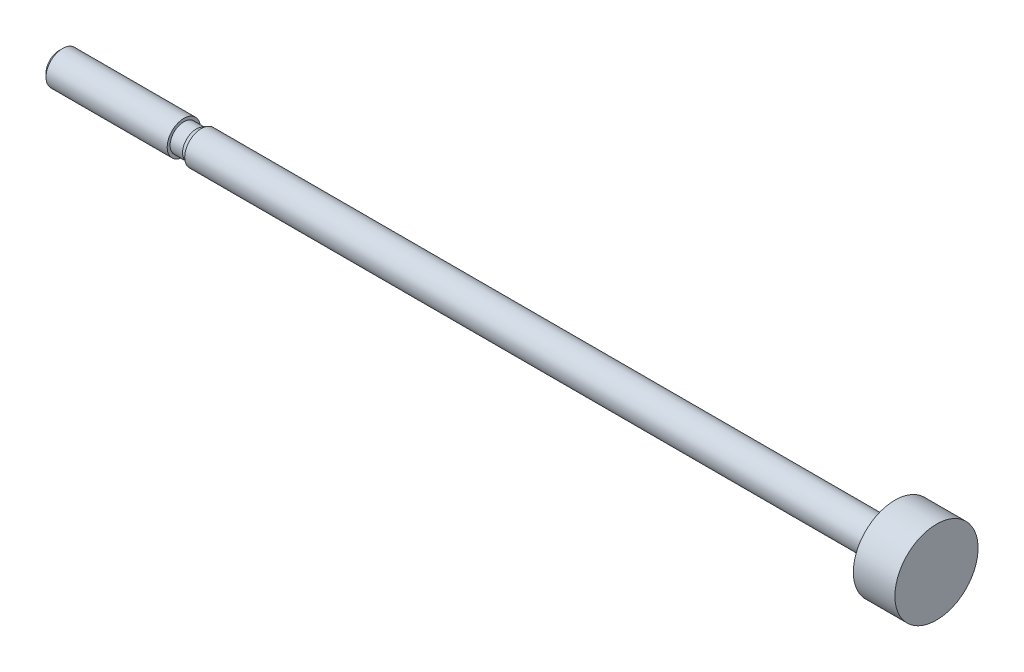
SolidWorks part; units mm, degrees
ref_plane "前视基准面" through (0, 0, 0) normal (0, 0, 1) x (1, 0, 0)
ref_plane "上视基准面" through (0, 0, 0) normal (0, 1, 0) x (1, 0, 0)
ref_plane "右视基准面" through (0, 0, 0) normal (1, 0, 0) x (0, 0, -1)
ref_plane "基准面1" through (0, 0, 0) normal (0, 0, 1) x (1, 0, 0)
sketch "草图1" plane through (0, 0, 0) normal (0, 0, 1) x (1, 0, 0)
  line L0 (0, 0) -> (0, 1.5705)
  line L1 (0, 1.5705) -> (0.4295, 2)
  line L2 (0.4295, 2) -> (15, 2)
  line L3 (15, 2) -> (15, 1.65)
  line L4 (15, 1.65) -> (16.5, 1.65)
  line L5 (16.5, 1.65) -> (17.1062, 2)
  line L6 (17.1062, 2) -> (100.5, 2)
  line L7 (100.5, 2) -> (100.5, 5)
  line L8 (100.5, 5) -> (105.5, 5)
  line L9 (105.5, 5) -> (105.5, 0)
  line L10 (105.5, 0) -> (0, 0)
  line L11 (105.5, 0) -> (0, 0) construction
revolve "旋转1" add sketch "草图1" angle 360 about L11
cosmetic thread "装饰螺纹线1"
